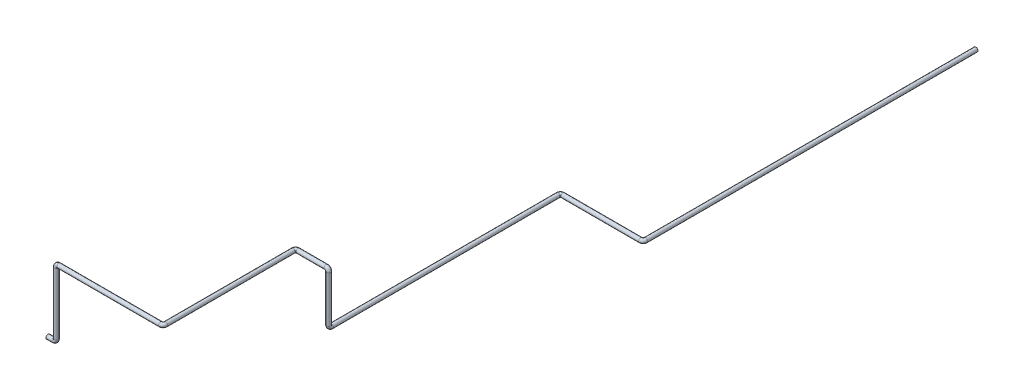
SolidWorks part; units mm, degrees
ref_plane "Alzado" through (0, 0, 0) normal (0, 0, 1) x (1, 0, 0)
ref_plane "Planta" through (0, 0, 0) normal (0, 1, 0) x (1, 0, 0)
ref_plane "Vista lateral" through (0, 0, 0) normal (1, 0, 0) x (0, 0, -1)
sketch "Croquis1" plane through (0, 0, 0) normal (0, 0, 1) x (1, 0, 0)
  circle A0 centre (0, 0) radius 12.7
  dimension "D1" = 25.4
extrude "Saliente-Extruir1" add sketch "Croquis1" along normal blind 10
sketch3d "Croquis3D1"
  line L0 (0, 0, 10) -> (0, 0, 1995)
  line L1 (0, 0, 10) -> (0, 0, 0) construction
  line L2 (-15, 0, 2010) -> (-485, 0, 2010)
  line L3 (-500, 0, 2025) -> (-500, 0, 3395)
  line L4 (-500, 15, 3410) -> (-500, 295, 3410)
  line L5 (-515, 310, 3410) -> (-685, 310, 3410)
  line L6 (-700, 310, 3425) -> (-700, 310, 4195)
  line L7 (-715, 310, 4210) -> (-1330, 310, 4210)
  line L8 (-1345, 295, 4210) -> (-1345, -80, 4210)
  line L9 (-1360, -95, 4210) -> (-1395, -95, 4210)
  arc A0 (-1345, -80, 4210) -> (-1360, -95, 4210) centre (-1360, -80, 4210) ccw
  arc A1 (-1330, 310, 4210) -> (-1345, 295, 4210) centre (-1330, 295, 4210) ccw
  arc A2 (-700, 310, 4195) -> (-715, 310, 4210) centre (-715, 310, 4195) ccw
  arc A3 (-685, 310, 3410) -> (-700, 310, 3425) centre (-685, 310, 3425) ccw
  arc A4 (-500, 295, 3410) -> (-515, 310, 3410) centre (-515, 295, 3410) ccw
  arc A5 (-500, 0, 3395) -> (-500, 15, 3410) centre (-500, 15, 3395) ccw
  arc A6 (-485, 0, 2010) -> (-500, 0, 2025) centre (-485, 0, 2025) ccw
  arc A7 (0, 0, 1995) -> (-15, 0, 2010) centre (-15, 0, 1995) ccw
  point P14 (-1345, -95, 4210)
  point P15 (-1360, -80, 4195)
  point P18 (-1345, 310, 4210)
  point P19 (-1330, 295, 4225)
  point P22 (-700, 310, 4210)
  point P23 (-715, 295, 4195)
  point P26 (-700, 310, 3410)
  point P27 (-685, 325, 3425)
  point P30 (-500, 310, 3410)
  point P31 (-515, 295, 3425)
  point P34 (-500, 0, 3410)
  point P35 (-515, 15, 3395)
  point P38 (-500, 0, 2010)
  point P39 (-485, 15, 2025)
  point P42 (0, 0, 2010)
  point P43 (-15, -15, 1995)
  dimension "D10" = 15
  dimension "D1" = 2000
  dimension "D2" = 500
  dimension "D3" = 1400
  dimension "D4" = 310
  dimension "D5" = 200
  dimension "D6" = 800
  dimension "D7" = 645
  dimension "D8" = 405
  dimension "D9" = 50
sketch "Croquis2" plane through (0, 0, 10) normal (0, 0, 1) x (1, 0, 0)
  circle A0 centre (0, 0) radius 12.7
  dimension "D1" = 25.4
sweep "Barrer1" add profiles "Croquis2" path "Croquis3D1"
sketch "Croquis3" plane through (0, 0, 0) normal (0, 0, -1) x (-1, 0, 0)
  line L1 (-0.0463, 12.6751) -> (0.0463, 12.6751)
  line L2 (-0.0463, 12.6751) -> (-0.0463, 12.7249)
  line L3 (-0.0463, 12.7249) -> (0.0463, 12.7249)
  line L4 (0.0463, 12.6751) -> (0.0463, 12.7249)
  line L5 (-0.0463, 12.6751) -> (0.0463, 12.7249) construction
  line L6 (-0.0463, 12.7249) -> (0.0463, 12.6751) construction
  circle A0 centre (0, 0) radius 12.7 construction
  point P0 (0, 12.7)
extrude "Saliente-Extruir2" add sketch "Croquis3" against normal blind 1
